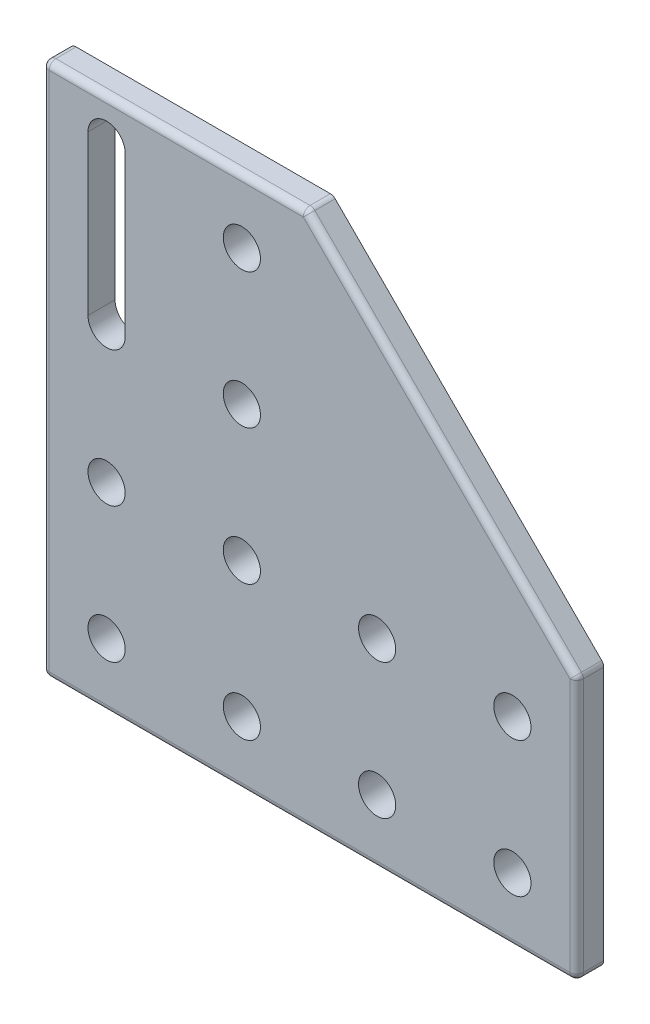
SolidWorks part; units mm, degrees
ref_plane "Front Plane" through (0, 0, 0) normal (0, 0, 1) x (1, 0, 0)
ref_plane "Top Plane" through (0, 0, 0) normal (0, 1, 0) x (1, 0, 0)
ref_plane "Right Plane" through (0, 0, 0) normal (1, 0, 0) x (0, 0, -1)
sketch "Sketch1" plane through (0, 0, 0) normal (0, 0, 1) x (1, 0, 0)
  line L0 (0, 0) -> (0, 79)
  line L1 (9.5, 9.5) -> (29.5, 9.5) construction
  line L2 (29.5, 9.5) -> (49.5, 9.5) construction
  line L3 (9.5, 9.5) -> (9.5, 29.5) construction
  line L4 (39, 79) -> (0, 79)
  line L5 (79, 0) -> (0, 0)
  line L6 (9.5, 29.5) -> (9.5, 49.5) construction
  line L7 (79, 39) -> (79, 0)
  line L8 (39, 79) -> (79, 39)
  line L9 (19.5, 69.5) -> (19.5, 79) construction
  line L10 (79, 19.5) -> (69.5, 19.5) construction
  line L11 (29.5, 9.5) -> (29.5, 29.5) construction
  line L12 (9.5, 69.5) -> (9.5, 49.5) construction
  line L13 (29.5, 29.5) -> (29.5, 49.5) construction
  line L14 (29.5, 49.5) -> (29.5, 69.5) construction
  line L15 (29.5, 69.5) -> (9.5, 69.5) construction
  line L16 (29.5, 49.5) -> (9.5, 49.5) construction
  line L17 (29.5, 29.5) -> (9.5, 29.5) construction
  line L18 (29.5, 29.5) -> (49.5, 29.5) construction
  line L19 (49.5, 29.5) -> (49.5, 9.5) construction
  line L20 (69.5, 9.5) -> (69.5, 29.5) construction
  line L21 (69.5, 29.5) -> (49.5, 29.5) construction
  line L22 (6.75, 73) -> (6.75, 49.5)
  line L23 (69.5, 9.5) -> (49.5, 9.5) construction
  line L24 (12.25, 73) -> (12.25, 49.5)
  circle A0 centre (9.5, 9.5) radius 2.75
  circle A1 centre (29.5, 9.5) radius 2.75
  circle A2 centre (49.5, 9.5) radius 2.75
  circle A3 centre (9.5, 29.5) radius 2.75
  arc A4 (6.75, 49.5) -> (12.25, 49.5) centre (9.5, 49.5) ccw construction
  circle A5 centre (69.5, 9.5) radius 2.75
  circle A6 centre (69.5, 29.5) radius 2.75
  circle A7 centre (49.5, 29.5) radius 2.75
  circle A8 centre (29.5, 29.5) radius 2.75
  circle A9 centre (29.5, 49.5) radius 2.75
  circle A10 centre (29.5, 69.5) radius 2.75
  circle A11 centre (9.5, 69.5) radius 2.75 construction
  arc A12 (6.75, 49.5) -> (12.25, 49.5) centre (9.5, 49.5) ccw
  arc A13 (12.25, 73) -> (6.75, 73) centre (9.5, 73) ccw
  dimension "D1" = 20
  dimension "E" = 5.5
  dimension "D2" = 9.5
  dimension "D5" = 5.5
  dimension "C" = 79
  dimension "D3" = 20
  dimension "B" = 79
  dimension "D4" = 9.5
  dimension "D6" = 23.5
extrude "Boss-Extrude1" add sketch "Sketch1" along normal mid plane 4
fillet "Fillet1" radius 1 10 edges at (0, 0, 0) (0, 39.5, 2) (39.5, 0, 2) (79, 19.5, 2) (79, 0, 0) (19.5, 79, 2) (0, 79, 0) (59, 59, 2) (79, 39, 0) (39, 79, 0)
